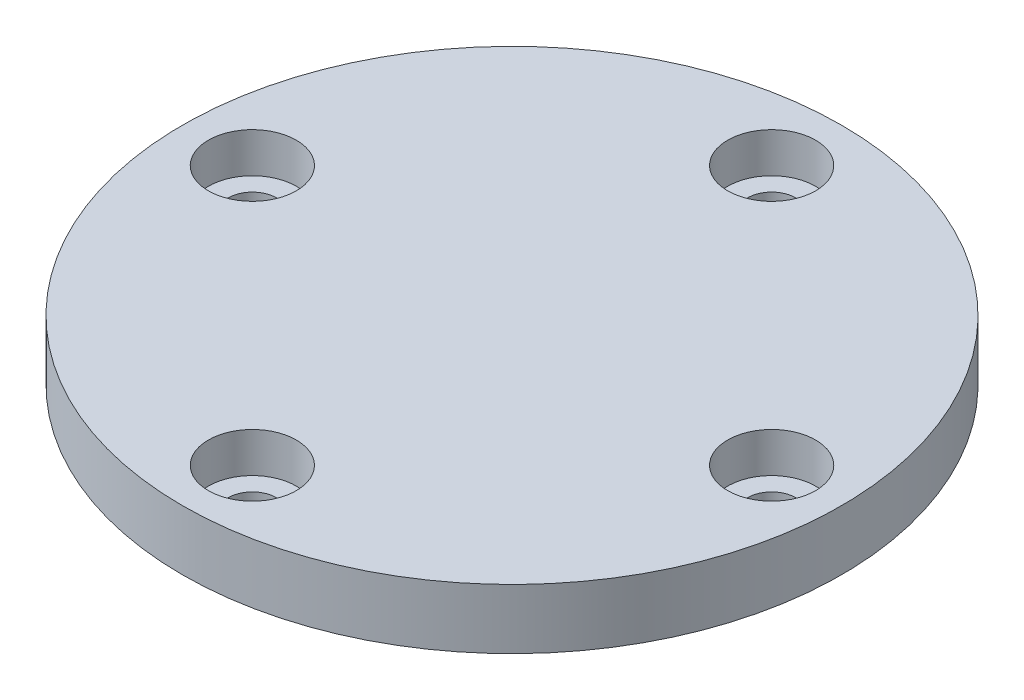
SolidWorks part; units mm, degrees
material "6061-T6 (SS)"
ref_plane "Front Plane" through (0, 0, 0) normal (0, 0, 1) x (1, 0, 0)
ref_plane "Top Plane" through (0, 0, 0) normal (0, 1, 0) x (1, 0, 0)
ref_plane "Right Plane" through (0, 0, 0) normal (1, 0, 0) x (0, 0, -1)
sketch "Sketch1" plane through (0, 0, 0) normal (0, 1, 0) x (1, 0, 0)
  circle A0 centre (0, 0) radius 16.5
  dimension "D1" = 33
extrude "Boss-Extrude1" add sketch "Sketch1" along normal blind 3
sketch "Sketch3" plane through (0, 3, 0) normal (0, 1, 0) x (1, 0, 0)
  circle A0 centre (0, -10.25) radius 0.25
  circle A1 centre (0, 0) radius 9.8
  dimension "D1" = 0.5
  dimension "D2" = 10.25
  dimension "D3" = 19.6
sketch "Sketch4" plane through (0, 3, 0) normal (0, -1, 0) x (1, 0, 0)
  line L0 (0, 0) -> (13.2597, 13.2597) construction
  circle A0 centre (7.7782, 7.7782) radius 1
  dimension "D2" = 2
  dimension "D1" = 11
sketch "Sketch5" plane through (0, 3, 0) normal (0, 1, 0) x (1, 0, 0)
  circle A0 centre (0, 0) radius 11
  dimension "D1" = 22
hole_wizard "CBORE for M2 SHCS1" positions "Sketch6" profile "Sketch7" counterbore size "M2" standard "ANSI Metric" end condition through all
sketch "Sketch6" plane through (0, 3, 0) normal (0, 1, 0) x (1, 0, 0)
  point P0 (13, 0)
  dimension "D1" = 13
sketch "Sketch7" plane through (13, 3, 0) normal (1, 0, 0) x (0, 0, 1)
  line L0 (0, 0) -> (0, 3)
  line L1 (0, 3) -> (1.2, 3)
  line L3 (1.2, 3) -> (1.2, 2)
  line L4 (1.2, 2) -> (2.2, 2)
  line L5 (2.2, 2) -> (2.2, 0)
  line L7 (2.2, 0) -> (0, 0)
  line L11 (0, -6.35) -> (0, 107.95) construction
  dimension "Thru Hole Dia." = 2.4
  dimension "Thru Hole Depth" = 3
  dimension "C'Bore Dia." = 4.4
  dimension "C'Bore Depth" = 2
pattern_circular "CirPattern1" count 4 over 360 about axis through (0, 0, 0) along (0, 1, 0) of "CBORE for M2 SHCS1"
sketch "Sketch8" plane through (0, 0, 0) normal (0, -1, 0) x (1, 0, 0)
  circle A0 centre (6, 0) radius 0.5
  dimension "D1" = 1
  dimension "D2" = 6
extrude "Cut-Extrude1" cut sketch "Sketch8" against normal blind 1.5
